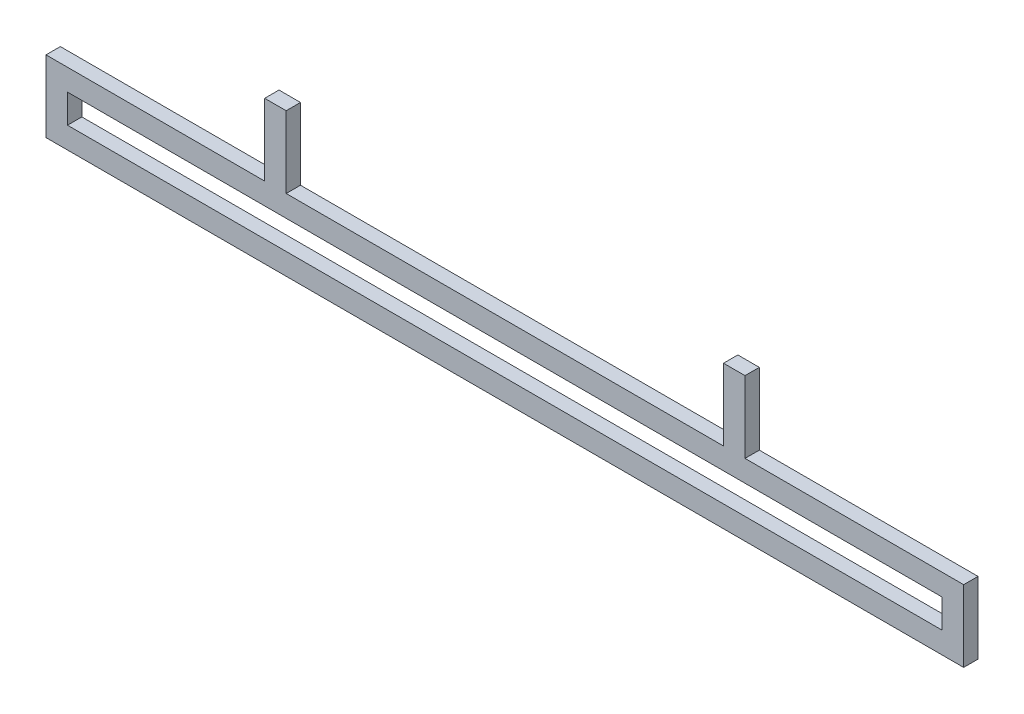
SolidWorks part; units mm, degrees
ref_plane "Front Plane" through (0, 0, 0) normal (0, 0, 1) x (1, 0, 0)
ref_plane "Top Plane" through (0, 0, 0) normal (0, 1, 0) x (1, 0, 0)
ref_plane "Right Plane" through (0, 0, 0) normal (1, 0, 0) x (0, 0, -1)
sketch "Sketch1" plane through (0, 0, 0) normal (0, 0, 1) x (1, 0, 0)
  line L1 (0, -145.36) -> (-640, -145.36)
  line L2 (0, -145.36) -> (0, -95.36)
  line L3 (0, -95.36) -> (-640, -95.36)
  line L4 (-640, -145.36) -> (-640, -95.36)
  dimension "D2" = 50
extrude "Boss-Extrude1" add sketch "Sketch1" along normal blind 10
sketch "Sketch2" plane through (0, 0, 0) normal (0, 0, 1) x (1, 0, 0)
  line L6 (-480, -145.36) -> (-480, -95.36) construction
  line L22 (-640, -95.36) -> (-640, -145.36) construction
  line L31 (-320, -145.36) -> (-320, -120.36) construction
  line L36 (-640, -145.36) -> (0, -145.36) construction
  line L37 (-320, -120.36) -> (-640, -120.36) construction
  line L38 (0, -95.36) -> (-640, -95.36) construction
  line L39 (-487.5, -95.36) -> (-472.5, -95.36)
  line L40 (-487.5, -95.36) -> (-487.5, -45.36)
  line L41 (-487.5, -45.36) -> (-472.5, -45.36)
  line L42 (-472.5, -95.36) -> (-472.5, -45.36)
  line L43 (-630, -45.36) -> (-487.5, -45.36) construction
  line L44 (-487.5, -95.36) -> (-487.5, -45.36)
  line L45 (-472.5, -95.36) -> (-472.5, -45.36)
  line L46 (-160, -145.36) -> (-160, -95.36) construction
  line L47 (-167.5, -95.36) -> (-167.5, -45.36)
  line L48 (-152.5, -95.36) -> (-152.5, -45.36)
  line L49 (-167.5, -95.36) -> (-167.5, -45.36)
  line L50 (-152.5, -45.36) -> (-167.5, -45.36)
  line L51 (-152.5, -95.36) -> (-152.5, -45.36)
  line L52 (-152.5, -95.36) -> (-167.5, -95.36)
  point P5 (-480, -120.36)
  point P19 (-480, -120.36)
  point P20 (-480, -95.36)
  line M30 (-640, -95.36) -> (0, -95.36)
  dimension "D1" = 15
extrude "Boss-Extrude2" add sketch "Sketch2" along normal blind 10 contours L50 L48 L47 M30 | L40 L39 L42 L41
sketch "Sketch3" plane through (0, 0, 0) normal (0, 0, -1) x (-1, 0, 0)
  line L0 (0, -95.36) -> (152.5, -95.36) construction
  line L1 (625, -110.36) -> (15, -110.36)
  line L2 (625, -110.36) -> (625, -130.36)
  line L3 (625, -130.36) -> (15, -130.36)
  line L4 (15, -110.36) -> (15, -130.36)
  line L5 (640, -145.36) -> (0, -145.36) construction
  line L6 (0, -145.36) -> (0, -95.36) construction
  line L7 (640, -95.36) -> (640, -145.36) construction
  dimension "D1" = 15
  dimension "D2" = 15
  dimension "D3" = 15
  dimension "D4" = 15
extrude "Cut-Extrude1" cut sketch "Sketch3" against normal blind 10 contours L2 L1 L4 L3
sketch "Sketch5" plane through (0, -45.36, 0) normal (0, 1, 0) x (1, 0, 0)
  line L0 (-160, -10) -> (-160, 0) construction
  line L1 (-152.5, -5) -> (-156.5, -5)
  line L2 (-152.5, -5) -> (-152.5, -10)
  line L3 (-152.5, -10) -> (-156.5, -10)
  line L4 (-156.5, -5) -> (-156.5, -10)
  line L5 (-152.5, -10) -> (-167.5, -10) construction
  line L6 (-152.5, 0) -> (-167.5, 0) construction
  line L7 (-163.5, -5) -> (-163.5, -10)
  line L8 (-167.5, -10) -> (-163.5, -10)
  line L9 (-167.5, -5) -> (-167.5, -10)
  line L10 (-167.5, -5) -> (-163.5, -5)
  dimension "D1" = 3.5
  dimension "D2" = 5
extrude "Cut-Extrude2" [suppressed] cut sketch "Sketch5" against normal blind 10
hole_wizard "CSK for M3 Countersunk Flat Head Screw1" [suppressed] positions "Sketch6" profile "Sketch7" countersink size "M3" standard "ISO"
sketch "Sketch6" plane through (0, 0, 10) normal (0, 0, 1) x (1, 0, 0)
  line L0 (-167.5, -50.36) -> (-152.5, -50.36) construction
  line L1 (-167.5, -55.36) -> (-167.5, -45.36) construction
  line L2 (-152.5, -95.36) -> (-152.5, -45.36) construction
  point P8 (-160, -50.36)
sketch "Sketch7" plane through (-160, -50.36, 10) normal (1, 0, 0) x (0, -1, 0)
  line L0 (0, 0) -> (0, 16.0215)
  line L1 (0, 16.0215) -> (1.7, 15)
  line L2 (1.7, 15) -> (1.7, 1.45)
  line L3 (1.7, 1.45) -> (3.15, 0)
  line L5 (3.15, 0) -> (0, 0)
  line L6 (-1.7, 1.45) -> (-3.15, 0) construction
  line L10 (0, 16.0215) -> (-1.7, 15) construction
  line L11 (0, -6.35) -> (0, 107.95) construction
  dimension "Hole Dia." = 3.4
  dimension "Hole Depth" = 15
  dimension "Near C'Sink Dia." = 6.3
  dimension "Near C'Sink Angle" = 90
  dimension "Drill Angle" = 118
